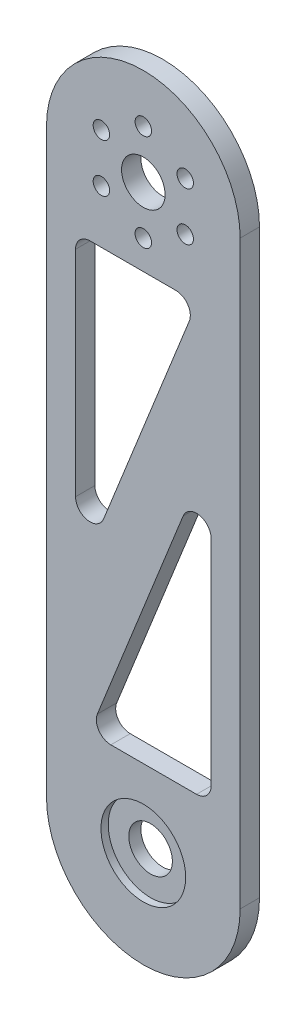
SolidWorks part; units mm, degrees
ref_plane "前视基准面" through (0, 0, 0) normal (0, 0, 1) x (1, 0, 0)
ref_plane "上视基准面" through (0, 0, 0) normal (0, 1, 0) x (1, 0, 0)
ref_plane "右视基准面" through (0, 0, 0) normal (1, 0, 0) x (0, 0, -1)
sketch "草图1" plane through (0, 0, 0) normal (0, 0, 1) x (1, 0, 0)
  line L0 (0, -43.0625) -> (0, 43.0625) construction
  line L1 (20, -60) -> (20, 60)
  line L3 (-20, 60) -> (-20, -60)
  arc A0 (20, 60) -> (-20, 60) centre (0, 60) ccw
  arc A1 (-20, -60) -> (20, -60) centre (0, -60) ccw
  circle A2 centre (0, 60) radius 4.5
  circle A3 centre (0, -60) radius 4.5
  point P4 (0, 0)
  dimension "D1" = 40
  dimension "D2" = 40
  dimension "D5" = 9
  dimension "D6" = 9
  dimension "D3" = 120
  dimension "D4" = 60
extrude "凸台-拉伸2" add sketch "草图1" along normal blind 4
sketch "草图4" plane through (0, 0, 4) normal (0, 0, 1) x (1, 0, 0)
  line L26 (20, -60) -> (20, 60) construction
  line L27 (-20, -50) -> (20, -50) construction
  line L28 (-20, -50) -> (-20, 50) construction
  line L29 (-20, 50) -> (20, 50) construction
  line L30 (20, -50) -> (20, 50) construction
  line L31 (-20, -50) -> (20, 50) construction
  line L32 (-20, 50) -> (20, -50) construction
  line L33 (-14, -18.8445) -> (11.1378, 44)
  line L34 (-14, 44) -> (11.1378, 44)
  line L35 (-14, -18.8445) -> (-14, 44)
  line L36 (14, -44) -> (14, 18.8445)
  line L37 (-11.1378, -44) -> (14, 18.8445)
  line L38 (-11.1378, -44) -> (14, -44)
  point P0 (0, 0)
  dimension "D1" = 100
  dimension "D2" = 6
  dimension "D3" = 6
extrude "切除-拉伸1" cut sketch "草图4" against normal through all
fillet "圆角1" radius 3 6 edges at (14, 18.8445, 2) (14, -44, 2) (-11.1378, -44, 2) (-14, -18.8445, 2) (11.1378, 44, 2) (-14, 44, 2)
sketch "草图6" plane through (0, 0, 4) normal (0, 0, 1) x (1, 0, 0)
  line L0 (0, -60) -> (0, 60) construction
  line L1 (0, 60) -> (8.6603, 55) construction
  line L3 (0, 60) -> (8.6603, 65) construction
  line L4 (0, 70) -> (0, 60) construction
  line L5 (-8.6603, 65) -> (0, 60) construction
  line L6 (0, 60) -> (-8.6603, 55) construction
  circle A0 centre (0, 50) radius 1.7
  circle A1 centre (-8.6603, 55) radius 1.7
  circle A2 centre (-8.6603, 65) radius 1.7
  circle A3 centre (0, 70) radius 1.7
  circle A4 centre (8.6603, 65) radius 1.7
  circle A5 centre (8.6603, 55) radius 1.7
  point P16 (0, 60)
  dimension "D1" = 3.4
  dimension "D5" = 10
  dimension "D2" = 10
  dimension "D3" = 60
  dimension "D4" = 6
extrude "切除-拉伸2" cut sketch "草图6" against normal through all
sketch "草图7" plane through (0, 0, 4) normal (0, 0, 1) x (1, 0, 0)
  circle A0 centre (0, -60) radius 8.75
  dimension "D1" = 17.5
extrude "切除-拉伸3" cut sketch "草图7" against normal blind 1.5
